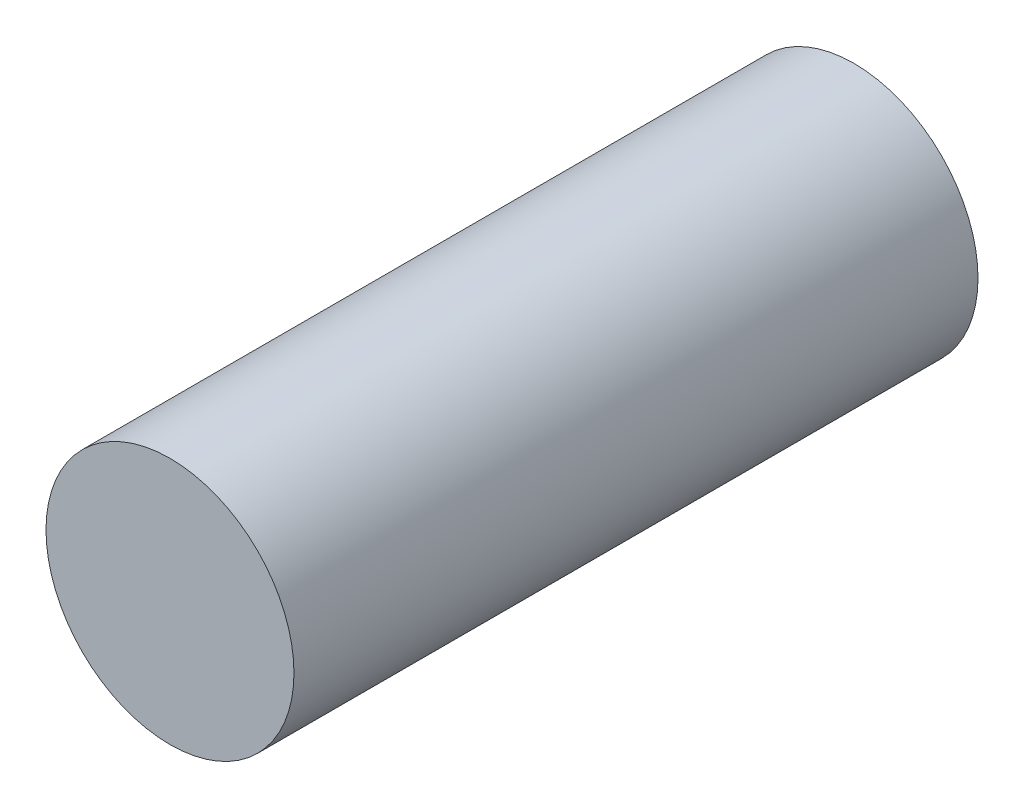
SolidWorks part; units mm, degrees
ref_plane "Front Plane" through (0, 0, 0) normal (0, 0, 1) x (1, 0, 0)
ref_plane "Top Plane" through (0, 0, 0) normal (0, 1, 0) x (1, 0, 0)
ref_plane "Right Plane" through (0, 0, 0) normal (1, 0, 0) x (0, 0, -1)
sketch "Sketch1" plane through (0, 0, 0) normal (0, 0, 1) x (1, 0, 0)
  circle A0 centre (0, 0) radius 1.45
  dimension "D1" = 2.9
extrude "Boss-Extrude1" add sketch "Sketch1" along normal blind 8
